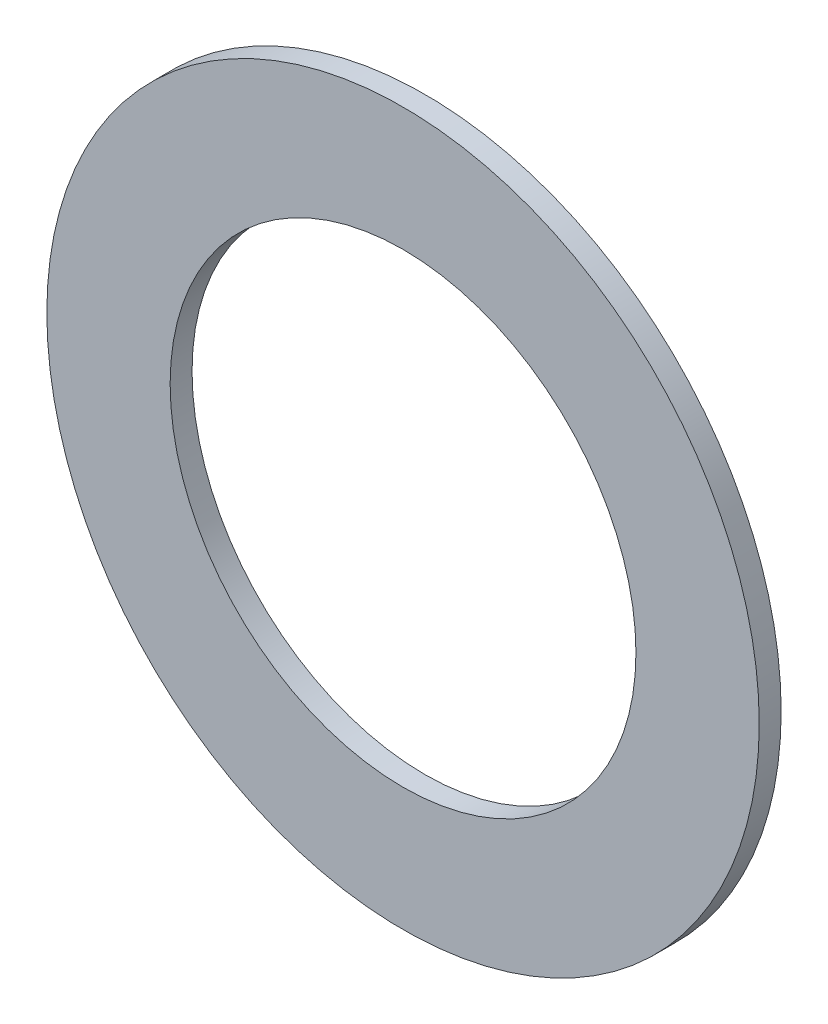
SolidWorks part; units mm, degrees
ref_plane "Front Plane" through (0, 0, 0) normal (0, 0, 1) x (1, 0, 0)
ref_plane "Top Plane" through (0, 0, 0) normal (0, 1, 0) x (1, 0, 0)
ref_plane "Right Plane" through (0, 0, 0) normal (1, 0, 0) x (0, 0, -1)
sketch "Sketch1" plane through (0, 0, 0) normal (0, 0, 1) x (1, 0, 0)
  circle A0 centre (0, 0) radius 32.5
  circle A1 centre (0, 0) radius 21.25
extrude "Boss-Extrude1" add sketch "Sketch1" along normal blind 2
